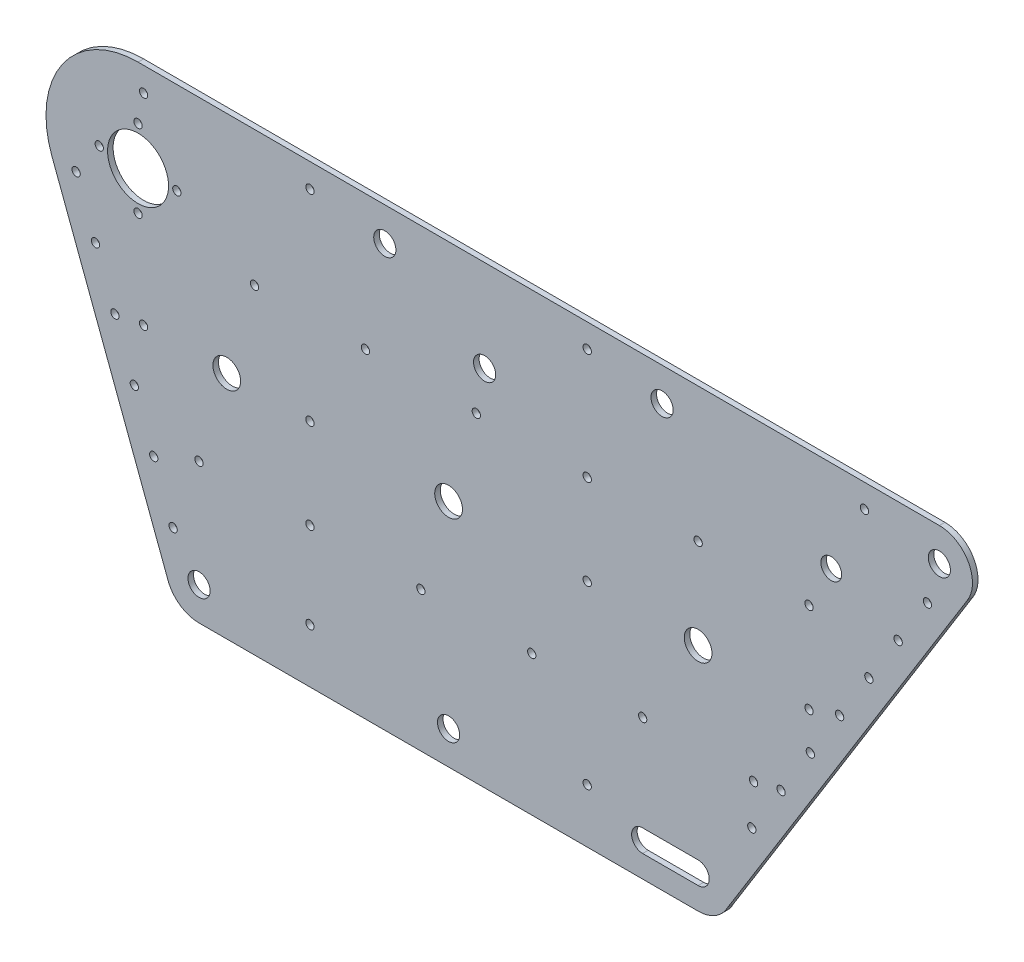
SolidWorks part; units mm, degrees
ref_plane "Front Plane" through (0, 0, 0) normal (0, 0, 1) x (1, 0, 0)
ref_plane "Top Plane" through (0, 0, 0) normal (0, 1, 0) x (1, 0, 0)
ref_plane "Right Plane" through (0, 0, 0) normal (1, 0, 0) x (0, 0, -1)
sketch "Sketch1" plane through (0, 0, 0) normal (0, 0, 1) x (1, 0, 0)
  line B0 (-105.2394, 83.4869) -> (-147.4084, -28.8454)
  ellipse B1 centre (-94.3313, 78.4869) end of major axis (-94.3313, 66.4869) minor radius 11.9994 (-94.3313, 90.4869) -> (-105.2394, 83.4869) ccw
  ellipse B2 centre (-94.3313, 78.4869) end of major axis (-94.3313, 74.4869) minor radius 3.9998
  ellipse B3 centre (-4.3358, 78.4869) end of major axis (-4.3358, 74.4869) minor radius 3.9998
  line B4 (85.6597, 74.4869) -> (65.6607, 74.4869)
  ellipse B5 centre (-103.6719, 65.3682) end of major axis (-103.6719, 66.8682) minor radius 1.4999
  ellipse B6 centre (-110.67, 46.6324) end of major axis (-110.67, 48.1324) minor radius 1.4999
  ellipse B7 centre (-94.3313, 39.9869) end of major axis (-94.3313, 38.4869) minor radius 1.4999
  ellipse B8 centre (-117.6679, 27.8973) end of major axis (-117.6679, 29.3973) minor radius 1.4999
  ellipse B9 centre (-114.3303, 7.4869) end of major axis (-114.3303, 5.9869) minor radius 1.4999
  ellipse B10 centre (-124.6658, 9.1621) end of major axis (-124.6658, 10.6621) minor radius 1.4999
  ellipse B11 centre (-131.6638, -9.5733) end of major axis (-131.6638, -11.0733) minor radius 1.4999
  ellipse B12 centre (-116.3302, -40.5131) end of major axis (-116.3302, -51.5131) minor radius 10.9995
  ellipse B13 centre (-116.3302, -26.5131) end of major axis (-116.3302, -28.0131) minor radius 1.4999
  ellipse B14 centre (-138.6618, -28.3089) end of major axis (-138.6618, -26.8089) minor radius 1.4999
  ellipse B15 centre (-130.3295, -40.5131) end of major axis (-130.3295, -42.0131) minor radius 1.4999
  ellipse B16 centre (-102.3309, -40.5131) end of major axis (-102.3309, -42.0131) minor radius 1.4999
  ellipse B17 centre (-116.3302, -54.5131) end of major axis (-116.3302, -56.0131) minor radius 1.4999
  ellipse B18 centre (-114.3303, -65.0131) end of major axis (-114.3303, -66.5131) minor radius 1.4999
  line B19 (172.6659, -73.4567) -> (-116.3024, -73.7108)
  ellipse B20 centre (-54.3333, -65.0131) end of major axis (-54.3333, -66.5131) minor radius 1.4999
  ellipse B21 centre (-27.3345, -61.5131) end of major axis (-27.3345, -65.5131) minor radius 3.9998
  ellipse B22 centre (-74.3323, -25.0131) end of major axis (-74.3323, -26.5131) minor radius 1.4999
  ellipse B23 centre (-84.3318, 7.4869) end of major axis (-84.3318, 2.4869) minor radius 4.9998
  ellipse B24 centre (-34.3343, -25.0131) end of major axis (-34.3343, -26.5131) minor radius 1.4999
  ellipse B25 centre (-54.3333, 39.9869) end of major axis (-54.3333, 38.4869) minor radius 1.4999
  ellipse B26 centre (-4.3358, 7.4869) end of major axis (-4.3358, 2.4869) minor radius 4.9997
  ellipse B27 centre (-14.3353, 39.9869) end of major axis (-14.3353, 38.4869) minor radius 1.4999
  ellipse B28 centre (5.6637, -25.0131) end of major axis (5.6637, -26.5131) minor radius 1.4999
  ellipse B29 centre (8.6636, -40.5131) end of major axis (8.6636, -44.5131) minor radius 3.9998
  ellipse B30 centre (45.6617, -25.0131) end of major axis (45.6617, -26.5131) minor radius 1.4999
  ellipse B31 centre (45.6617, 7.4869) end of major axis (45.6617, 5.9869) minor radius 1.4999
  ellipse B32 centre (25.6627, 39.9869) end of major axis (25.6627, 38.4869) minor radius 1.4999
  ellipse B33 centre (45.6617, 70.9869) end of major axis (45.6617, 69.4869) minor radius 1.4999
  ellipse B34 centre (65.6607, 39.9869) end of major axis (65.6607, 38.4869) minor radius 1.4999
  ellipse B35 centre (133.6573, -40.5131) end of major axis (133.6573, -44.2631) minor radius 3.7498
  ellipse B36 centre (72.6604, -61.5131) end of major axis (72.6604, -65.5131) minor radius 3.9998
  ellipse B37 centre (85.6597, -25.0131) end of major axis (85.6597, -26.5131) minor radius 1.4999
  ellipse B38 centre (45.6617, -65.0131) end of major axis (45.6617, -66.5131) minor radius 1.4999
  ellipse B39 centre (125.6577, -25.0131) end of major axis (125.6577, -26.5131) minor radius 1.4999
  ellipse B40 centre (145.6567, -65.0131) end of major axis (145.6567, -66.5131) minor radius 1.4999
  ellipse B41 centre (172.6554, -61.5131) end of major axis (172.6554, -73.4567) minor radius 11.943 (172.6659, -73.4567) -> (182.7461, -55.1244) ccw
  ellipse B42 centre (168.3499, -47.1115) end of major axis (168.3499, -48.6115) minor radius 1.4999
  ellipse B43 centre (157.7954, -30.1237) end of major axis (157.7954, -31.6237) minor radius 1.4999
  ellipse B44 centre (147.241, -13.1361) end of major axis (147.241, -14.6361) minor radius 1.4999
  ellipse B45 centre (136.6861, 3.8522) end of major axis (136.6861, 2.3522) minor radius 1.4999
  ellipse B46 centre (125.6577, 7.4869) end of major axis (125.6577, 5.9869) minor radius 1.4999
  ellipse B47 centre (85.6597, 7.4869) end of major axis (85.6597, 2.4869) minor radius 4.9997
  ellipse B48 centre (126.1314, 20.8403) end of major axis (126.1314, 19.3403) minor radius 1.4999
  ellipse B49 centre (115.5769, 37.8281) end of major axis (115.5769, 36.3281) minor radius 1.4999
  ellipse B50 centre (105.6587, 39.9869) end of major axis (105.6587, 38.4869) minor radius 1.4999
  line B51 (96.3607, 83.9155) -> (182.7461, -55.1244)
  ellipse B52 centre (105.0226, 54.8156) end of major axis (105.0226, 53.3156) minor radius 1.4999
  line B53 (-94.3313, 90.4869) -> (85.6597, 90.4869)
  line B54 (65.6607, 82.4869) -> (85.6597, 82.4869)
  ellipse B55 centre (65.6607, 78.4869) end of major axis (65.6607, 74.4869) minor radius 3.9998 (65.6607, 82.4869) -> (65.6607, 74.4869) ccw
  ellipse B56 centre (85.6597, 78.4869) end of major axis (85.6597, 74.4869) minor radius 3.9998 (85.6597, 74.4869) -> (85.6597, 82.4869) ccw
  ellipse B57 centre (-116.3302, -40.5131) end of major axis (-116.3302, -73.7108) minor radius 33.196 (-147.4084, -28.8454) -> (-116.301, -73.7108) ccw
  ellipse B58 centre (85.6597, 78.4869) end of major axis (85.6597, 66.4869) minor radius 11.9994 (96.3626, 83.9124) -> (85.6597, 90.4869) ccw
sketch_block_instance "BodyOutline-1"
sketch_block "Block1"
sketch "Sketch2" plane through (0, 0, 0) normal (0, 0, 1) x (1, 0, 0)
  line L0 (65.6607, 82.4869) -> (85.6597, 82.4869)
  line L1 (85.6597, 74.4869) -> (65.6607, 74.4869)
  line L2 (96.3626, 83.9124) -> (182.7461, -55.1244)
  line L4 (172.6658, -73.4563) -> (-116.3011, -73.7093)
  line L6 (-147.4084, -28.8454) -> (-105.2394, 83.4869)
  line L7 (-94.3313, 90.4864) -> (85.6387, 90.4864)
  circle A0 centre (-94.3313, 78.4869) radius 3.9998
  circle A1 centre (-4.3358, 78.4869) radius 3.9998
  circle A2 centre (-54.3333, 70.9869) radius 1.4999
  circle A3 centre (-103.6719, 65.3682) radius 1.4999
  circle A4 centre (-110.67, 46.6324) radius 1.4999
  circle A5 centre (-94.3313, 39.9869) radius 1.4999
  circle A6 centre (-117.6679, 27.8973) radius 1.4999
  circle A7 centre (-114.3303, 7.4869) radius 1.4999
  circle A8 centre (-124.6658, 9.1621) radius 1.4999
  circle A9 centre (-131.6638, -9.5733) radius 1.4999
  circle A10 centre (-116.3302, -26.5131) radius 1.4999
  circle A11 centre (-138.6618, -28.3089) radius 1.4999
  circle A12 centre (-130.3295, -40.5131) radius 1.4999
  circle A13 centre (-102.3309, -40.5131) radius 1.4999
  circle A14 centre (-114.3303, -65.0131) radius 1.4999
  circle A15 centre (-116.3302, -54.5131) radius 1.4999
  circle A16 centre (8.6636, -40.5131) radius 3.9998
  circle A17 centre (-54.3333, -65.0131) radius 1.4999
  circle A18 centre (-27.3345, -61.5131) radius 3.9998
  circle A19 centre (-74.3323, -25.0131) radius 1.4999
  circle A20 centre (-84.3318, 7.4869) radius 4.9998
  circle A21 centre (-54.3333, 7.4869) radius 1.4999
  circle A22 centre (-34.3343, -25.0131) radius 1.4999
  circle A23 centre (-54.3333, 39.9869) radius 1.4999
  circle A24 centre (-14.3353, 39.9869) radius 1.4999
  circle A25 centre (-4.3358, 7.4869) radius 4.9997
  circle A26 centre (5.6637, -25.0131) radius 1.4999
  circle A27 centre (85.6597, -25.0131) radius 1.4999
  circle A28 centre (45.6617, -25.0131) radius 1.4999
  circle A29 centre (45.6617, 7.4869) radius 1.4999
  circle A30 centre (25.6627, 39.9869) radius 1.4999
  circle A31 centre (45.6617, 70.9869) radius 1.4999
  circle A32 centre (65.6607, 39.9869) radius 1.4999
  arc A33 (-147.4084, -28.8454) -> (-116.3011, -73.7093) centre (-116.3302, -40.5131) ccw
  circle A34 centre (72.6604, -61.5131) radius 3.9998
  circle A35 centre (45.6617, -65.0131) radius 1.4999
  circle A36 centre (125.6577, -25.0131) radius 1.4999
  circle A37 centre (133.6573, -40.5131) radius 3.7498
  circle A38 centre (145.6567, -65.0131) radius 1.4999
  circle A39 centre (172.6554, -61.5131) radius 3.9998
  circle A40 centre (168.3499, -47.1115) radius 1.4999
  circle A41 centre (157.7954, -30.1237) radius 1.4999
  circle A42 centre (147.241, -13.1361) radius 1.4999
  circle A43 centre (136.6861, 3.8522) radius 1.4999
  circle A44 centre (125.6577, 7.4869) radius 1.4999
  circle A45 centre (85.6597, 7.4869) radius 4.9997
  circle A46 centre (126.1314, 20.8403) radius 1.4999
  circle A47 centre (115.5769, 37.8281) radius 1.4999
  circle A48 centre (105.6587, 39.9869) radius 1.5
  circle A49 centre (105.0226, 54.8156) radius 1.4999
  circle A50 centre (-116.3302, -40.5131) radius 10.9995
  arc A51 (-105.2394, 83.4869) -> (-94.3313, 90.4864) centre (-94.3313, 78.4869) cw
  arc A52 (96.3626, 83.9124) -> (85.6387, 90.4864) centre (85.6597, 78.4869) ccw
  arc A53 (85.6597, 74.4869) -> (85.6597, 82.4869) centre (85.6597, 78.4869) ccw
  arc A54 (65.6607, 82.4869) -> (65.6607, 74.4869) centre (65.6607, 78.4869) ccw
  arc A55 (182.7461, -55.1244) -> (172.6658, -73.4563) centre (172.6554, -61.5131) cw
  ellipse E0 centre (85.6597, 78.4869) end of major axis (85.6597, 74.4869) minor radius 3.9998 (85.6597, 74.4869) -> (85.6597, 82.4869) ccw construction
  ellipse E2 centre (65.6607, 78.4869) end of major axis (65.6607, 74.4869) minor radius 3.9998 (65.6607, 82.4869) -> (65.6607, 74.4869) ccw construction
extrude "Boss-Extrude1" add sketch "Sketch2" along normal mid plane 2
move or copy body "Body-Move/Copy1" bodies to move or copy 102 copy no rotation origin (0, 8.3885, 0) rotation axis (1, 0, 0) rotation angle 180
